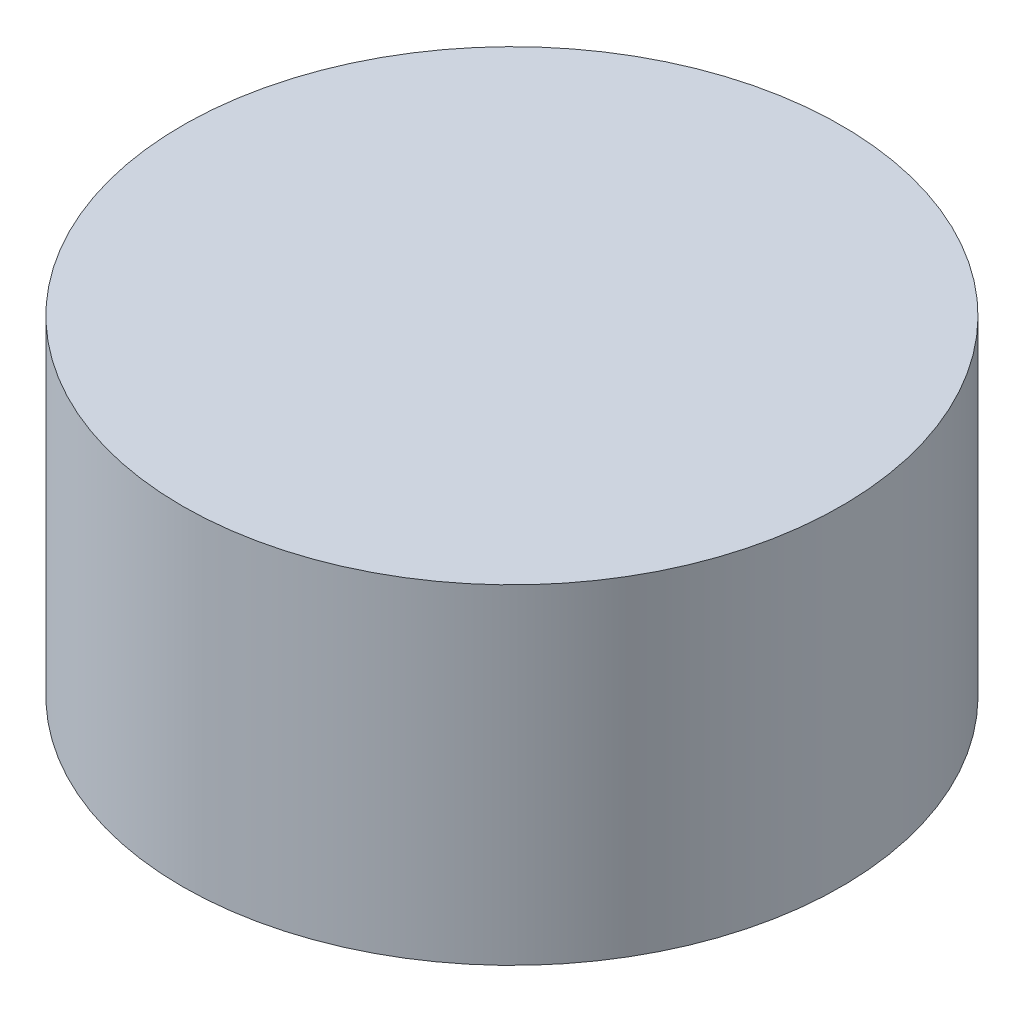
SolidWorks part; units mm, degrees
ref_plane "前视基准面" through (0, 0, 0) normal (0, 0, 1) x (1, 0, 0)
ref_plane "上视基准面" through (0, 0, 0) normal (0, 1, 0) x (1, 0, 0)
ref_plane "右视基准面" through (0, 0, 0) normal (1, 0, 0) x (0, 0, -1)
other "Configuration Table"
sketch "草图1" plane through (0, 0, 0) normal (0, 1, 0) x (1, 0, 0)
  circle A0 centre (0, 0) radius 5
  dimension "D1" = 10
extrude "凸台-拉伸1" add sketch "草图1" along normal blind 5
